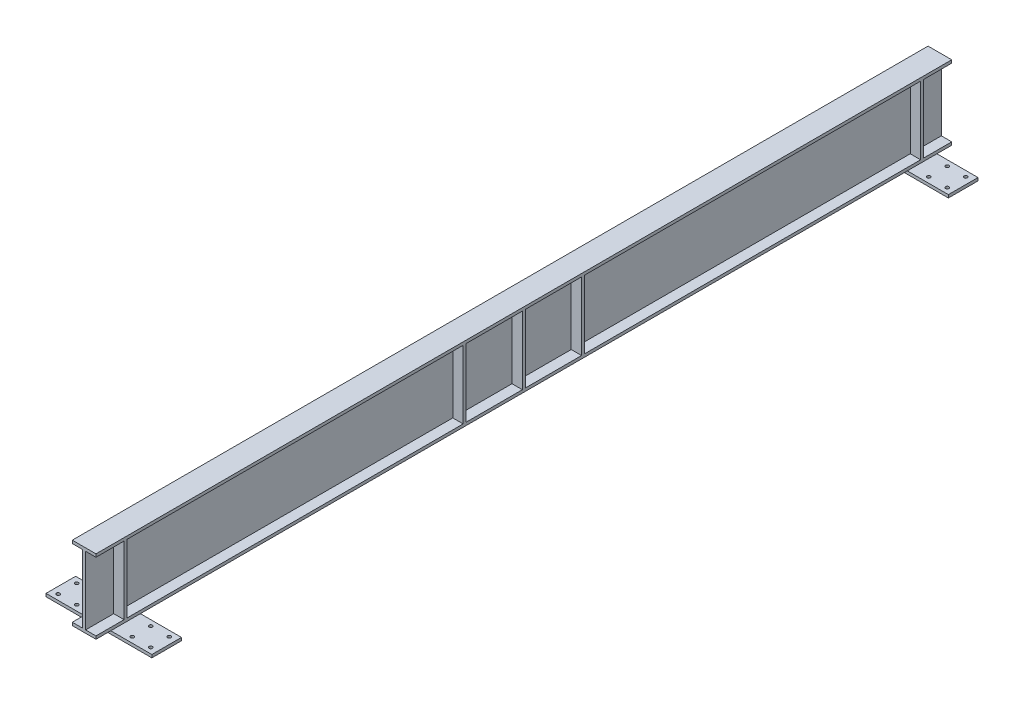
SolidWorks part; units mm, degrees
ref_plane "前视基准面" through (0, 0, 0) normal (0, 0, 1) x (1, 0, 0)
ref_plane "上视基准面" through (0, 0, 0) normal (0, 1, 0) x (1, 0, 0)
ref_plane "右视基准面" through (0, 0, 0) normal (1, 0, 0) x (0, 0, -1)
sketch "草图1" plane through (0, 0, 0) normal (0, 0, -1) x (1, 0, 0)
  line L0 (0, 0) -> (160, 0)
  line L1 (160, 0) -> (160, 20)
  line L2 (160, 20) -> (90, 20)
  line L3 (90, 20) -> (90, 480)
  line L4 (90, 480) -> (160, 480)
  line L5 (160, 480) -> (160, 500)
  line L6 (160, 500) -> (0, 500)
  line L7 (0, 500) -> (0, 480)
  line L8 (0, 480) -> (70, 480)
  line L9 (70, 480) -> (70, 20)
  line L10 (70, 20) -> (0, 20)
  line L11 (0, 20) -> (0, 0)
  line L12 (80, -1000) -> (80, 49000) construction
  point P16 (80, 0)
  dimension "D1" = 500
  dimension "D2" = 20
  dimension "D3" = 20
  dimension "D4" = 20
  dimension "D5" = 160
  dimension "D6" = 160
extrude "凸台-拉伸1" add sketch "草图1" along normal blind 5780
sketch "草图2" plane through (160, 0, 0) normal (1, 0, 0) x (0, 0, -1)
  line L0 (5780, -20) -> (0, -20) construction
  line L1 (190, -20) -> (210, -20)
  line L2 (190, -20) -> (190, -480)
  line L3 (190, -480) -> (210, -480)
  line L4 (210, -20) -> (210, -480)
  line L5 (5780, -480) -> (0, -480) construction
  line L6 (5780, -20) -> (0, -20) construction
  line L7 (2480, -20) -> (2500, -20)
  line L8 (2480, -20) -> (2480, -480)
  line L9 (2480, -480) -> (2500, -480)
  line L10 (2500, -20) -> (2500, -480)
  line L11 (2880, -20) -> (2900, -20)
  line L12 (2880, -20) -> (2880, -480)
  line L13 (2880, -480) -> (2900, -480)
  line L14 (2900, -20) -> (2900, -480)
  line L15 (200, -1480) -> (200, 48520) construction
  line L16 (3280, -20) -> (3300, -20)
  line L17 (3280, -20) -> (3280, -480)
  line L18 (3280, -480) -> (3300, -480)
  line L19 (3300, -20) -> (3300, -480)
  line L20 (5570, -20) -> (5590, -20)
  line L21 (5570, -20) -> (5570, -480)
  line L22 (5570, -480) -> (5590, -480)
  line L23 (5590, -20) -> (5590, -480)
  line L24 (2490, -1480) -> (2490, 48520) construction
  line L25 (2890, -1480) -> (2890, 48520) construction
  line L26 (3290, -1480) -> (3290, 48520) construction
  line L27 (5580, -1480) -> (5580, 48520) construction
  line L28 (0, -20) -> (0, -480) construction
  line L29 (5780, -20) -> (5780, -480) construction
  line L30 (2890, -1000) -> (2890, 49000) construction
  line L31 (5780, 0) -> (0, 0) construction
  point P29 (200, -480)
  point P32 (2490, -480)
  point P35 (2890, -480)
  point P38 (3290, -480)
  point P41 (5580, -480)
  point P50 (2890, 0)
  dimension "D1" = 20
  dimension "D2" = 200
  dimension "D3" = 400
  dimension "D4" = 400
  dimension "D5" = 200
extrude "凸台-拉伸2" add sketch "草图2" against normal blind 160
sketch "草图3" plane through (0, -500, 0) normal (0, -1, 0) x (1, 0, 0)
  line L0 (-1218.2781, -5580) -> (48781.7219, -5580) construction
  line L1 (-277.5, -5480) -> (437.5, -5480)
  line L2 (-277.5, -5480) -> (-277.5, -5680)
  line L3 (-277.5, -5680) -> (437.5, -5680)
  line L4 (437.5, -5480) -> (437.5, -5680)
  line L5 (80, -6500) -> (80, 43500) construction
  line L6 (160, -5780) -> (0, -5780) construction
  line L7 (-1096.9877, -200) -> (48903.0123, -200) construction
  line L8 (-277.5, -100) -> (437.5, -100)
  line L9 (-277.5, -100) -> (-277.5, -300)
  line L10 (-277.5, -300) -> (437.5, -300)
  line L11 (437.5, -100) -> (437.5, -300)
  line L12 (160, 0) -> (0, 0) construction
  point P7 (-277.5, -5580)
  point P12 (80, -5780)
  point P19 (-277.5, -200)
  dimension "D1" = 200
  dimension "D2" = 200
  dimension "D3" = 715
  dimension "D4" = 200
  dimension "D5" = 200
  dimension "D6" = 715
extrude "凸台-拉伸3" add sketch "草图3" along normal blind 20
sketch "草图4" plane through (0, -520, 0) normal (0, -1, 0) x (1, 0, 0)
  line L0 (-1277.5, -200) -> (48722.5, -200) construction
  line L1 (-277.5, -100) -> (-277.5, -300) construction
  line L2 (80, -1100) -> (80, 48900) construction
  line L3 (437.5, -100) -> (-277.5, -100) construction
  circle A0 centre (-232.5, -137.5) radius 11.5
  circle A1 centre (-232.5, -262.5) radius 11.5
  circle A2 centre (-107.5, -137.5) radius 11.5
  circle A3 centre (-107.5, -262.5) radius 11.5
  circle A4 centre (267.5, -137.5) radius 11.5
  circle A5 centre (267.5, -262.5) radius 11.5
  circle A6 centre (392.5, -137.5) radius 11.5
  circle A7 centre (392.5, -262.5) radius 11.5
  point P5 (-277.5, -200)
  point P10 (80, -100)
  dimension "D1" = 23
  dimension "D2" = 125
  dimension "D3" = 375
  dimension "D4" = 125
extrude "切除-拉伸1" cut sketch "草图4" against normal blind 20
pattern_linear "阵列(线性)1" count 2 spacing 5380 along (0, 0, -1) of "切除-拉伸1"
